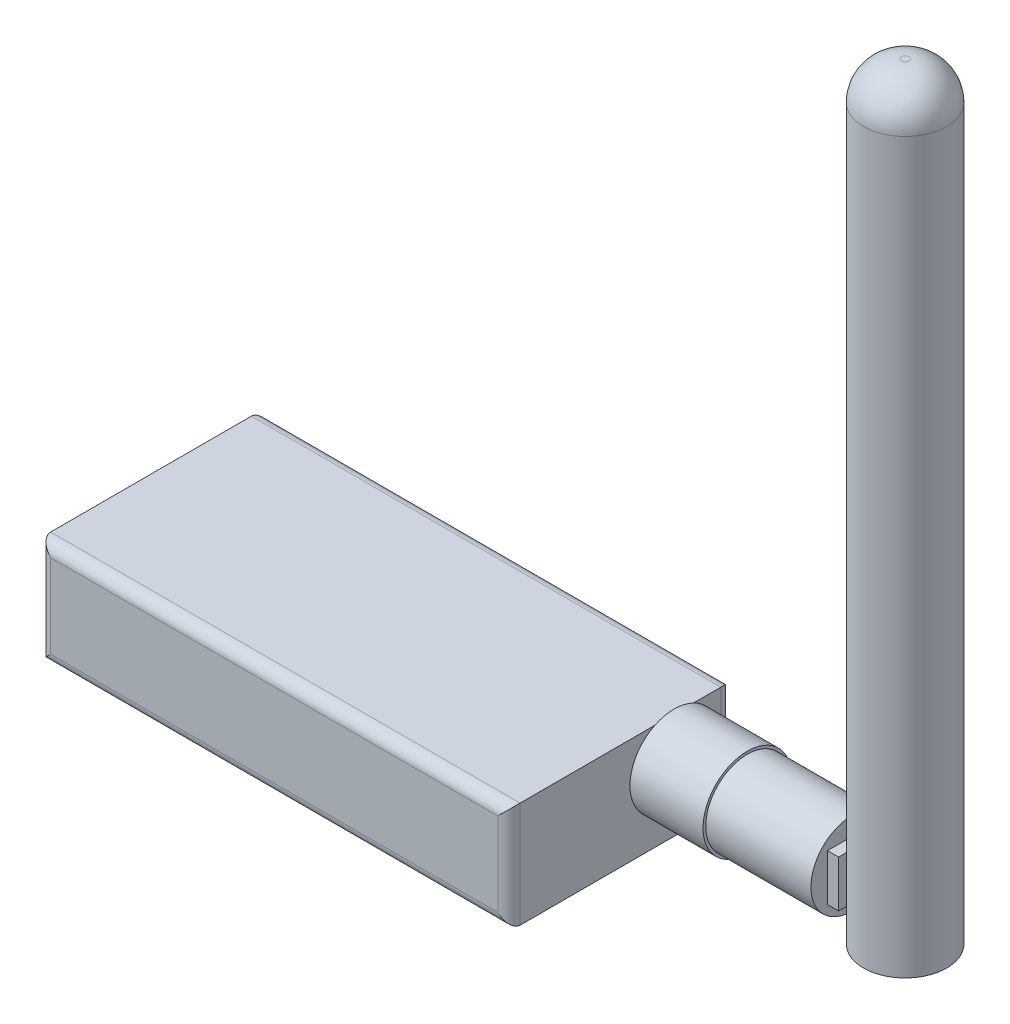
SolidWorks part; units mm, degrees
ref_plane "Front Plane" through (0, 0, 0) normal (0, 0, 1) x (1, 0, 0)
ref_plane "Top Plane" through (0, 0, 0) normal (0, 1, 0) x (1, 0, 0)
ref_plane "Right Plane" through (0, 0, 0) normal (1, 0, 0) x (0, 0, -1)
sketch "Sketch1" plane through (0, 0, 0) normal (0, 1, 0) x (1, 0, 0)
  line L1 (-26.1041, 14.7291) -> (27.4159, 14.7291)
  line L2 (-26.1041, 14.7291) -> (-26.1041, -10.6909)
  line L3 (-26.1041, -10.6909) -> (27.4159, -10.6909)
  line L4 (27.4159, 14.7291) -> (27.4159, -10.6909)
  dimension "D1" = 53.52
  dimension "D2" = 25.42
extrude "Boss-Extrude2" add sketch "Sketch1" along normal blind 12.06 contours L1 L4 L3 L2
sketch "Sketch2" plane through (27.4159, 0, 0) normal (1, 0, 0) x (0, 0, -1)
  line L0 (14.7291, 0) -> (-10.6909, 0) construction
  line L1 (-10.6909, 12.06) -> (-10.6909, 0) construction
  circle A0 centre (8.1513, 7.5138) radius 5.05
  dimension "D1" = 10.1
  dimension "D2" = 7.5138
  dimension "D3" = 18.8422
extrude "Boss-Extrude3" add sketch "Sketch2" along normal blind 8.33
sketch "Sketch3" plane through (35.7459, 0, 0) normal (1, 0, 0) x (0, 0, -1)
  circle A0 centre (8.1513, 7.5138) radius 4.745
  arc A1 (5.9526, 12.06) -> (10.3501, 12.06) centre (8.1513, 7.5138) ccw construction
fillet "Fillet2" radius 1.27 4 edges at (-26.1041, 6.03, 10.6909) (0.6559, 12.06, 10.6909) (27.4159, 6.03, 10.6909) (0.6559, 0, 10.6909)
fillet "Fillet3" radius 1.27 4 edges at (27.4159, 6.03, -14.7291) (0.6559, 12.06, -14.7291) (-26.1041, 6.03, -14.7291) (0.6559, 0, -14.7291)
sketch3d "3DSketch1"
  circle A0 centre (35.7459, 7.5138, -8.1513) radius 4.745
  point P2 (40.4909, 7.5138, -8.1513)
extrude "Boss-Extrude4" add sketch "Sketch3" along normal blind 12 contours A0
sketch "Sketch4" plane through (47.7459, 0, 0) normal (1, 0, 0) x (0, 0, -1)
  line L1 (5.2913, 10.1738) -> (11.0113, 10.1738)
  line L2 (5.2913, 10.1738) -> (5.2913, 4.8538)
  line L3 (5.2913, 4.8538) -> (11.0113, 4.8538)
  line L4 (11.0113, 10.1738) -> (11.0113, 4.8538)
  line L5 (5.2913, 10.1738) -> (11.0113, 4.8538) construction
  line L6 (5.2913, 4.8538) -> (11.0113, 10.1738) construction
  point P0 (8.1513, 7.5138)
  point P6 (0, 0)
  point P7 (0, 0)
  point P8 (0, 0)
  point P9 (0, 0)
  point P10 (0, 0)
  dimension "D1" = 5.32
  dimension "D2" = 5.72
ref_plane "Plane5" through (0, 2.54, 0) normal (0, 1, 0) x (1, 0, 0)
sketch "Sketch10" plane through (0, 2.54, 0) normal (0, 1, 0) x (1, 0, 0)
  line L0 (47.7459, 5.2913) -> (47.7459, 11.0113) construction
  circle A0 centre (53.7609, 8.128) radius 4.745
  point P2 (0, 0)
  point P3 (0, 0)
  point P4 (0, 0)
  dimension "D1" = 6.015
extrude "Boss-Extrude8" add sketch "Sketch10" along normal blind 87.4 separate body contours A0
fillet "Fillet4" radius 4.318 1 edges at (53.7609, 89.94, -3.383)
extrude "Boss-Extrude9" add sketch "Sketch4" along normal blind 1.27 contours L4 L3 L2 L1
